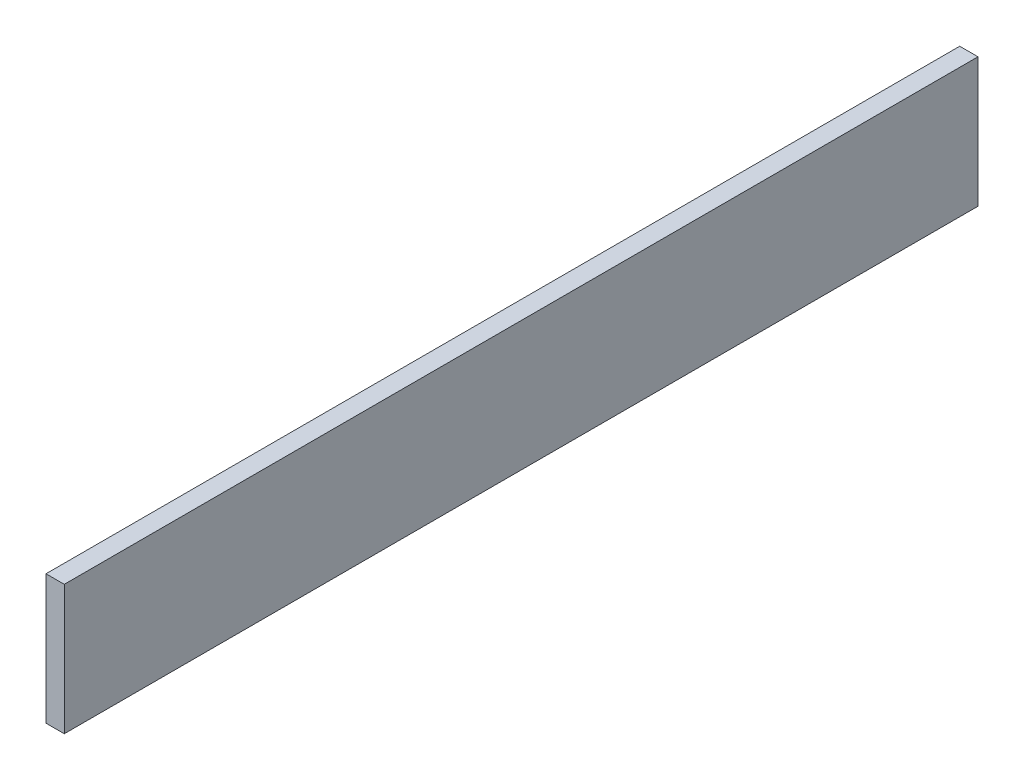
SolidWorks part; units mm, degrees
material "CA"
ref_plane "Front Plane" through (0, 0, 0) normal (0, 0, 1) x (1, 0, 0)
ref_plane "Top Plane" through (0, 0, 0) normal (0, 1, 0) x (1, 0, 0)
ref_plane "Right Plane" through (0, 0, 0) normal (1, 0, 0) x (0, 0, -1)
sketch "Sketch1" plane through (0, 0, 0) normal (1, 0, 0) x (0, 0, -1)
  line L1 (-150, 21.25) -> (150, 21.25)
  line L2 (-150, 21.25) -> (-150, -21.25)
  line L3 (-150, -21.25) -> (150, -21.25)
  line L4 (150, 21.25) -> (150, -21.25)
  point P4 (0, 21.25)
  point P5 (150, 0)
  dimension "D1" = 300
  dimension "D2" = 42.5
extrude "Boss-Extrude1" add sketch "Sketch1" along normal blind 6
